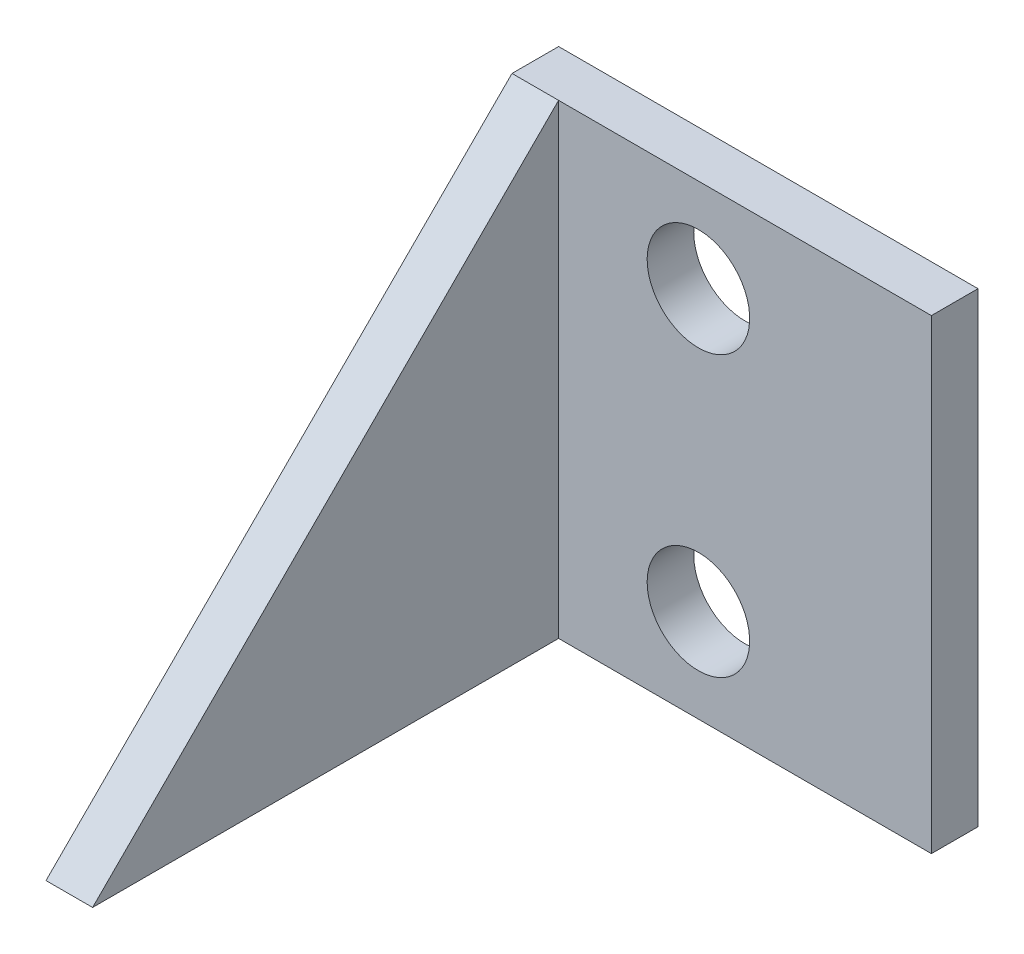
SolidWorks part; units mm, degrees
ref_plane "Front Plane" through (0, 0, 0) normal (0, 0, 1) x (1, 0, 0)
ref_plane "Top Plane" through (0, 0, 0) normal (0, 1, 0) x (1, 0, 0)
ref_plane "Right Plane" through (0, 0, 0) normal (1, 0, 0) x (0, 0, -1)
ref_plane "Plane1" through (-12, 0, 0) normal (1, 0, 0) x (0, 0, -1)
sketch "Sketch1" plane through (-12, 0, 0) normal (1, 0, 0) x (0, 0, -1)
  line L0 (-3, 15) -> (-33, -15)
  line L1 (-33, -15) -> (0, -15)
  line L2 (0, -15) -> (0, 15)
  line L3 (0, 15) -> (-3, 15)
extrude "Boss-Extrude1" add sketch "Sketch1" against normal blind 3
sketch "Sketch2" plane through (-12, 0, 0) normal (1, 0, 0) x (0, 0, -1)
  line L0 (-3, 15) -> (0, 15)
  line L1 (0, 15) -> (0, -15)
  line L2 (0, -15) -> (-3, -15)
  line L3 (-3, -15) -> (-3, 15)
extrude "Boss-Extrude2" add sketch "Sketch2" along normal blind 24
sketch "Sketch5" plane through (0, 0, 0) normal (0, 0, -1) x (-1, 0, 0)
  line L0 (15, -15) -> (-12, -15) construction
  line L1 (15, 15) -> (-12, 15) construction
  line L2 (-12, -15) -> (-12, 15) construction
  circle A0 centre (3, 9) radius 3.3
  circle A1 centre (3, -9) radius 3.3
  dimension "D1" = 6.6
  dimension "D2" = 6.6
  dimension "D3" = 6
  dimension "D4" = 6
  dimension "D5" = 15
  dimension "D6" = 15
extrude "Cut-Extrude1" cut sketch "Sketch5" against normal blind 10
